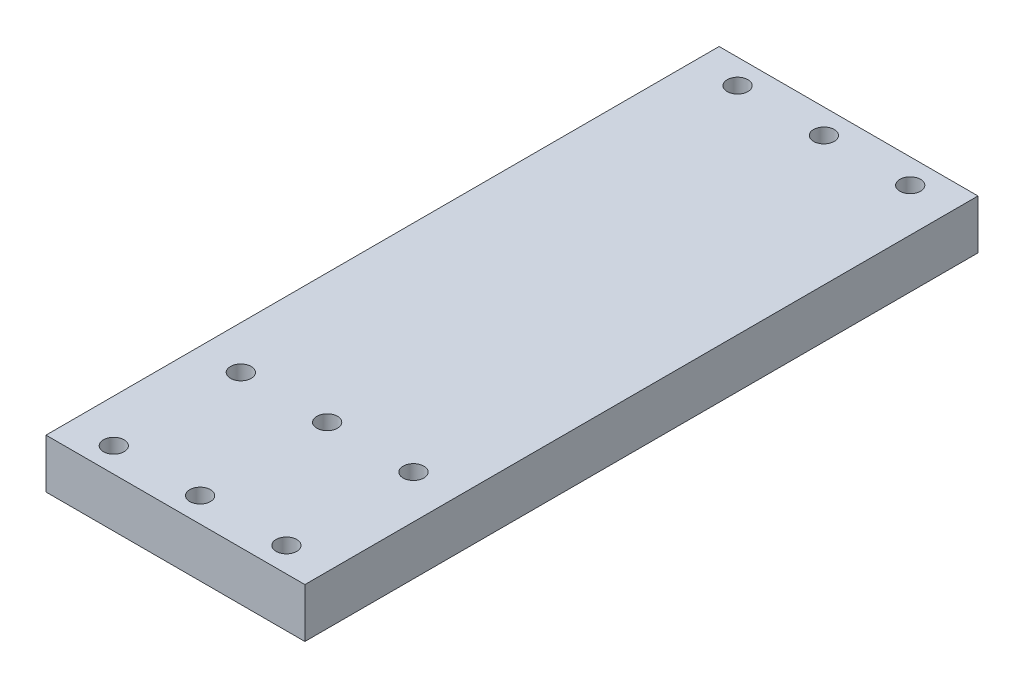
SolidWorks part; units mm, degrees
ref_plane "Front Plane" through (0, 0, 0) normal (0, 0, 1) x (1, 0, 0)
ref_plane "Top Plane" through (0, 0, 0) normal (0, 1, 0) x (1, 0, 0)
ref_plane "Right Plane" through (0, 0, 0) normal (1, 0, 0) x (0, 0, -1)
sketch "Sketch2" plane through (0, 0, 0) normal (0, 1, 0) x (1, 0, 0)
  line L1 (-25, -65) -> (25, -65)
  line L2 (-25, -65) -> (-25, 65)
  line L3 (-25, 65) -> (25, 65)
  line L4 (25, -65) -> (25, 65)
  line L5 (-25, -65) -> (25, 65) construction
  line L6 (-25, 65) -> (25, -65) construction
  point P0 (0, 0)
  dimension "D1" = 130
  dimension "D2" = 50
extrude "Boss-Extrude1" add sketch "Sketch2" along normal blind 9.525
sketch "Sketch3" plane through (0, 9.525, 0) normal (0, 1, 0) x (1, 0, 0)
  circle A0 centre (16.67, -60.2375) radius 2 construction
  circle A1 centre (0, -60.2375) radius 2 construction
  circle A2 centre (-16.67, -60.2375) radius 2 construction
  circle A3 centre (16.67, -35.7) radius 1.65 construction
  circle A4 centre (0, -35.7) radius 1.65 construction
  circle A5 centre (-16.67, -35.7) radius 1.65 construction
  circle A6 centre (16.67, 60.2375) radius 2 construction
  circle A7 centre (0, 60.2375) radius 2 construction
  circle A8 centre (-16.67, 60.2375) radius 2 construction
  circle A9 centre (16.67, -60.2375) radius 2
  circle A10 centre (0, -60.2375) radius 2
  circle A11 centre (-16.67, -60.2375) radius 2
  circle A12 centre (16.67, -35.7) radius 1.65
  circle A13 centre (0, -35.7) radius 1.65
  circle A14 centre (-16.67, -35.7) radius 1.65
  circle A15 centre (16.67, 60.2375) radius 2
  circle A16 centre (0, 60.2375) radius 2
  circle A17 centre (-16.67, 60.2375) radius 2
  point P29 (-16.67, 60.2375)
  point P32 (0, 60.2375)
  point P35 (16.67, 60.2375)
  point P38 (16.67, -35.7)
  point P41 (0, -35.7)
  point P44 (-16.67, -35.7)
  point P47 (-16.67, -60.2375)
  point P50 (0, -60.2375)
  point P53 (16.67, -60.2375)
hole_wizard "Ø4.0mm Dowel Hole1" positions "Sketch3" profile "Sketch5" hole size "Ø4.0" standard "ANSI Metric" end condition through all
sketch "Sketch5" plane through (16.67, 9.525, 60.2375) normal (1, 0, 0) x (0, 0, 1)
  line L0 (0, 0) -> (0, 9.525)
  line L1 (0, 9.525) -> (2, 9.525)
  line L2 (2, 9.525) -> (2, 0)
  line L5 (2, 0) -> (0, 0)
  line L11 (0, -6.35) -> (0, 107.95) construction
  dimension "Thru Hole Dia." = 4
  dimension "Thru Hole Depth" = 9.525
